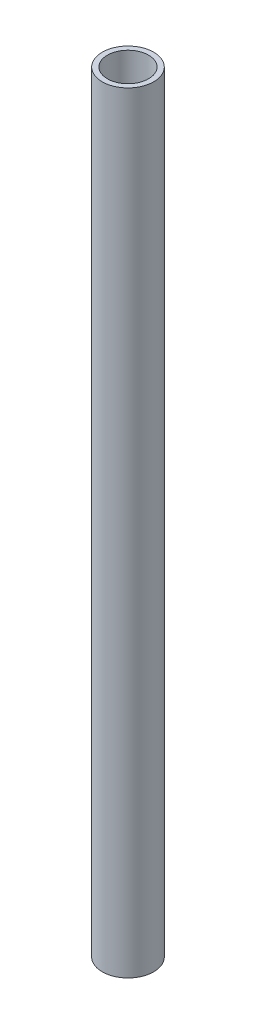
SolidWorks part; units mm, degrees
ref_plane "Plan de face" through (0, 0, 0) normal (0, 0, 1) x (1, 0, 0)
ref_plane "Plan de dessus" through (0, 0, 0) normal (0, 1, 0) x (1, 0, 0)
ref_plane "Plan de droite" through (0, 0, 0) normal (1, 0, 0) x (0, 0, -1)
sketch "Esquisse1" plane through (0, 0, 0) normal (0, 1, 0) x (1, 0, 0)
  circle A0 centre (0, 0) radius 5
  circle A1 centre (0, 0) radius 4
  dimension "D1" = 10
  dimension "D2" = 8
extrude "Boss.-Extru.1" add sketch "Esquisse1" along normal blind 150
